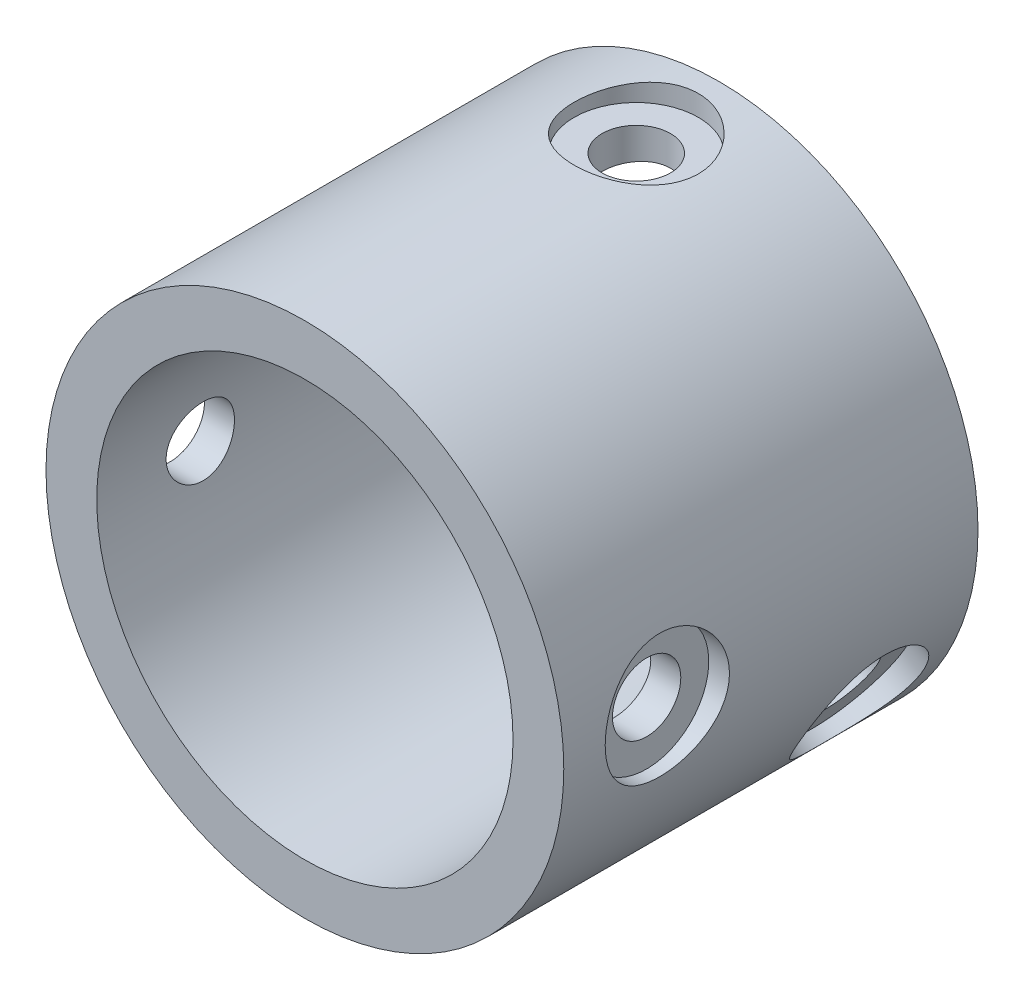
SolidWorks part; units mm, degrees
ref_plane "Front Plane" through (0, 0, 0) normal (0, 0, 1) x (1, 0, 0)
ref_plane "Top Plane" through (0, 0, 0) normal (0, 1, 0) x (1, 0, 0)
ref_plane "Right Plane" through (0, 0, 0) normal (1, 0, 0) x (0, 0, -1)
sketch "Sketch1" plane through (0, 0, 0) normal (0, 0, 1) x (1, 0, 0)
  circle A0 centre (0, 0) radius 10.05
  circle A1 centre (0, 0) radius 12.5
  dimension "D1" = 20.1
  dimension "D2" = 2.45
extrude "Boss-Extrude1" add sketch "Sketch1" along normal blind 20
sketch "Sketch2" plane through (0, 0, 20) normal (0, 0, 1) x (1, 0, 0)
  line L0 (0, 0) -> (0, 12.5) construction
  line L1 (0, 0) -> (10.8253, -6.25) construction
  line L2 (0, 0) -> (-10.8253, -6.25) construction
  line L3 (0, 0) -> (12.5, 0) construction
  line L4 (12.5, 0) -> (-12.5, 0) construction
  circle A0 centre (0, 0) radius 12.5 construction
  dimension "D1" = 120
  dimension "D2" = 120
ref_plane "Plane1" through (-10.8253, -6.25, 0) normal (-0.866, -0.5, 0) x (0, 0, 1)
ref_plane "Plane4" through (-12.5, 0, 0) normal (-1, 0, 0) x (0, 0, 1)
sketch "Sketch3" plane through (-10.8253, -6.25, 0) normal (-0.866, -0.5, 0) x (0, 0, 1)
  line L0 (0, 0) -> (20, 0) construction
  line L1 (20, 0) -> (20, 10.8253) construction
  line L2 (20, 0) -> (20, -10.8253) construction
  circle A0 centre (4, 0) radius 1.65
  dimension "D4" = 3.3
  dimension "D1" = 4
extrude "Cut-Extrude1" cut sketch "Sketch3" against normal blind 4
pattern_circular "CirPattern1" count 3 over 360 about axis through (0, 0, 0) along (0, 0, 1) of "Cut-Extrude1"
sketch "Sketch5" plane through (-10.8253, -6.25, 0) normal (-0.866, -0.5, 0) x (0, 0, 1)
  circle A0 centre (4, 0) radius 3
  dimension "D1" = 6
extrude "Cut-Extrude3" cut sketch "Sketch5" against normal blind 1
pattern_circular "CirPattern2" count 3 over 360 about axis through (0, 0, 0) along (0, 0, 1) of "Cut-Extrude3"
sketch "Sketch7" plane through (-12.5, 0, 0) normal (-1, 0, 0) x (0, 0, 1)
  line L0 (20, 0) -> (20, -6.25) construction
  circle A0 centre (15, 0) radius 1.65
  dimension "D1" = 3.3
  dimension "D2" = 5
extrude "Cut-Extrude5" cut sketch "Sketch7" against normal through all both and the other way through all
sketch "Sketch8" plane through (-12.5, 0, 0) normal (-1, 0, 0) x (0, 0, 1)
  circle A0 centre (15, 0) radius 3
  dimension "D1" = 6
extrude "Cut-Extrude6" cut sketch "Sketch8" against normal blind 1
pattern_circular "CirPattern6" count 2 over 360 about axis through (0, 0, 20) along (0, 0, -1) of "Cut-Extrude6"
